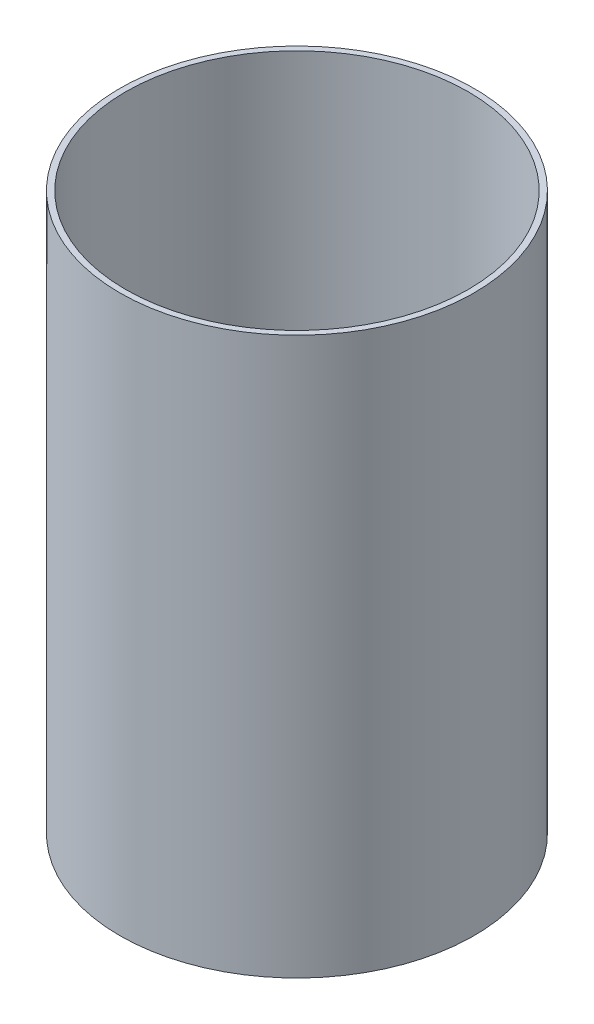
SolidWorks part; units mm, degrees
material "Thornel Mat VMA"
ref_plane "Front Plane" through (0, 0, 0) normal (0, 0, 1) x (1, 0, 0)
ref_plane "Top Plane" through (0, 0, 0) normal (0, 1, 0) x (1, 0, 0)
ref_plane "Right Plane" through (0, 0, 0) normal (1, 0, 0) x (0, 0, -1)
sketch "Sketch1" plane through (0, 0, 0) normal (0, 1, 0) x (1, 0, 0)
  circle A0 centre (0, 0) radius 45.5
  circle A1 centre (0, 0) radius 44
  dimension "D1" = 91
  dimension "D2" = 88
extrude "Boss-Extrude1" add sketch "Sketch1" along normal blind 143
